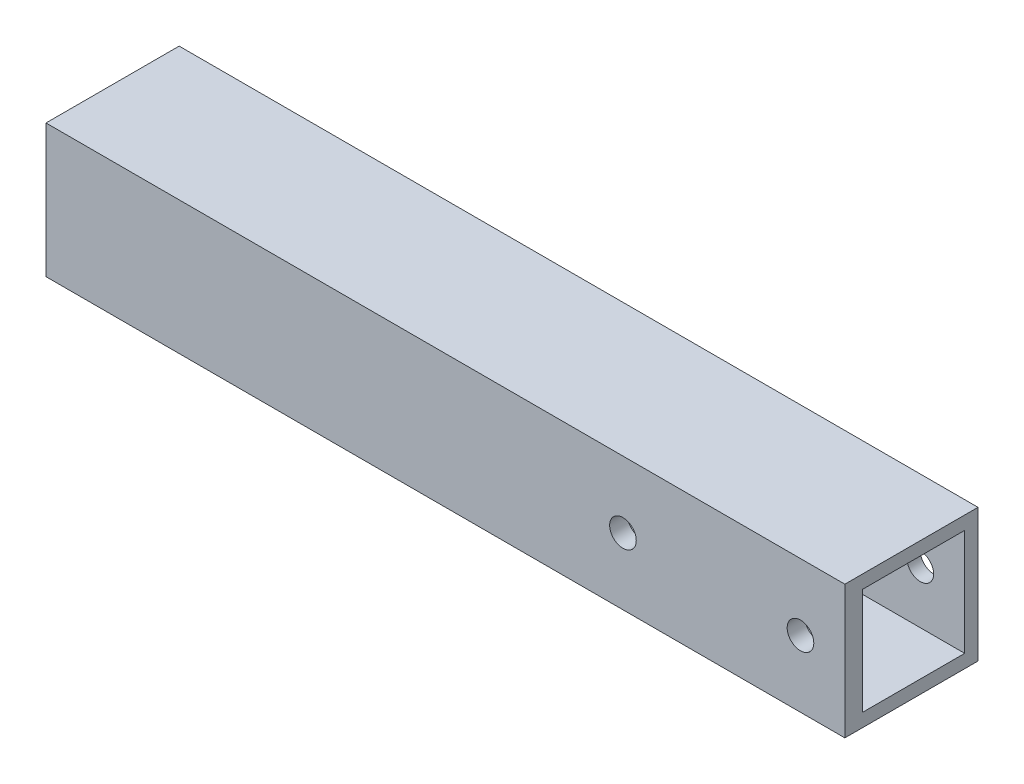
SolidWorks part; units mm, degrees
material "6061 合金"
ref_plane "前视基准面" through (0, 0, 0) normal (0, 0, 1) x (1, 0, 0)
ref_plane "上视基准面" through (0, 0, 0) normal (0, 1, 0) x (1, 0, 0)
ref_plane "右视基准面" through (0, 0, 0) normal (1, 0, 0) x (0, 0, -1)
sketch3d "3D草图1"
  line L0 (0, 0, 0) -> (90, 0, 0)
  dimension "D1" = 90
other "方形管 15 ×15× 1.5(1)"
ref_plane "基准面1" through (0, 0, 0) normal (1, 0, 0) x (0, 0, -1)
sketch "Sketch1" plane through (0, 0, 0) normal (1, 0, 0) x (0, 0, -1)
  line L0 (-4, -6) -> (4, -6)
  line L1 (-5.5, -3.5) -> (-5.5, 3.5)
  line L2 (3.5, 6) -> (-3.5, 6)
  line L3 (6, 3.5) -> (6, -3.5)
  line L4 (-6, -7.5) -> (6, -7.5)
  line L5 (-7.5, -6) -> (-7.5, 6)
  line L6 (6, 7.5) -> (-6, 7.5)
  line L7 (7.5, 6) -> (7.5, -6)
  line L8 (-5.5, 3.5) -> (-5.5, 6)
  line L9 (-5.5, 6) -> (-3.5, 6)
  line L10 (-7.5, 6) -> (-7.5, 7.5)
  line L11 (-7.5, 7.5) -> (-6, 7.5)
  line L12 (6, 7.5) -> (7.5, 7.5)
  line L13 (7.5, 7.5) -> (7.5, 6)
  line L14 (3.5, 6) -> (6, 6)
  line L15 (6, 6) -> (6, 3.5)
  line L16 (4, -6) -> (6, -6)
  line L17 (6, -6) -> (6, -3.5)
  line L18 (7.5, -6) -> (7.5, -7.5)
  line L19 (7.5, -7.5) -> (6, -7.5)
  line L20 (-5.5, -3.5) -> (-5.5, -6)
  line L21 (-5.5, -6) -> (-4, -6)
  line L22 (-7.5, -6) -> (-7.5, -7.5)
  line L23 (-7.5, -7.5) -> (-6, -7.5)
  line L24 (0, 7.5) -> (0, -7.5) construction
  line L25 (-7.5, 0) -> (7.5, 0) construction
  point P0 (-7.5, 0)
  point P1 (7.5, 0)
  point P2 (0, 7.5)
  point P3 (0, -7.5)
  point P4 (0, 0)
  point P5 (-7.5, -7.5)
  point P6 (7.5, -7.5)
  point P7 (7.5, 7.5)
  point P8 (-7.5, 7.5)
  point P38 (6, 0)
  point P39 (-5.5, 0)
  point P40 (0, 6)
  point P41 (0, -6)
  point P42 (0, 0)
  dimension "D1" = 1.5
  dimension "D2" = 1.5
  dimension "D3" = 1.5
  dimension "D4" = 1.5
  dimension "D5" = 1.5
  dimension "D6" = 12
  dimension "D7" = 1.5
  dimension "D8" = 1.5
  dimension "Thickness" = 2
  dimension "D9" = 1.5
  dimension "D10" = 1.5
sketch "草图3" plane through (0, 0, 7.5) normal (0, 0, 1) x (1, 0, 0)
  line L0 (90, 0) -> (0, 0) construction
  line L1 (90, 7.5) -> (90, -7.5) construction
  circle A0 centre (85, 0) radius 1.5
  circle A1 centre (65, 0) radius 1.5
  dimension "D1" = 20
  dimension "D3" = 3
  dimension "D2" = 5
extrude "切除-拉伸1" cut sketch "草图3" against normal through all
